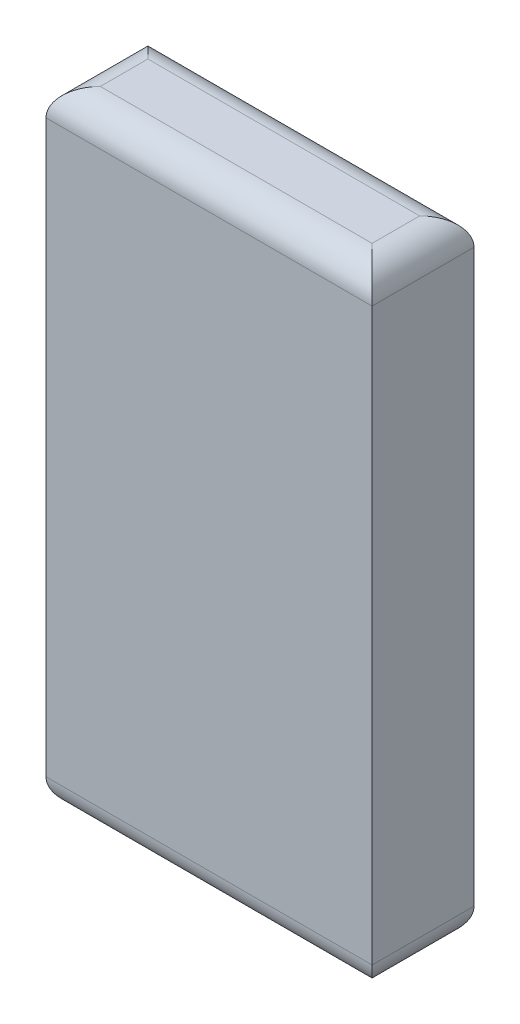
SolidWorks part; units mm, degrees
ref_plane "Front Plane" through (0, 0, 0) normal (0, 0, 1) x (1, 0, 0)
ref_plane "Top Plane" through (0, 0, 0) normal (0, 1, 0) x (1, 0, 0)
ref_plane "Right Plane" through (0, 0, 0) normal (1, 0, 0) x (0, 0, -1)
sketch "Sketch1" plane through (0, 0, 0) normal (0, 0, 1) x (1, 0, 0)
  line L1 (0, 0) -> (30.48, 0)
  line L2 (0, 0) -> (0, 58.42)
  line L3 (0, 58.42) -> (30.48, 58.42)
  line L4 (30.48, 0) -> (30.48, 58.42)
  dimension "D1" = 30.48
  dimension "D2" = 58.42
extrude "Boss-Extrude1" add sketch "Sketch1" along normal blind 9.525
fillet "Fillet1" radius 2.54 8 edges at (0, 0, 4.7625) (15.24, 0, 9.525) (30.48, 0, 4.7625) (15.24, 0, 0) (30.48, 58.42, 4.7625) (15.24, 58.42, 9.525) (0, 58.42, 4.7625) (15.24, 58.42, 0)
